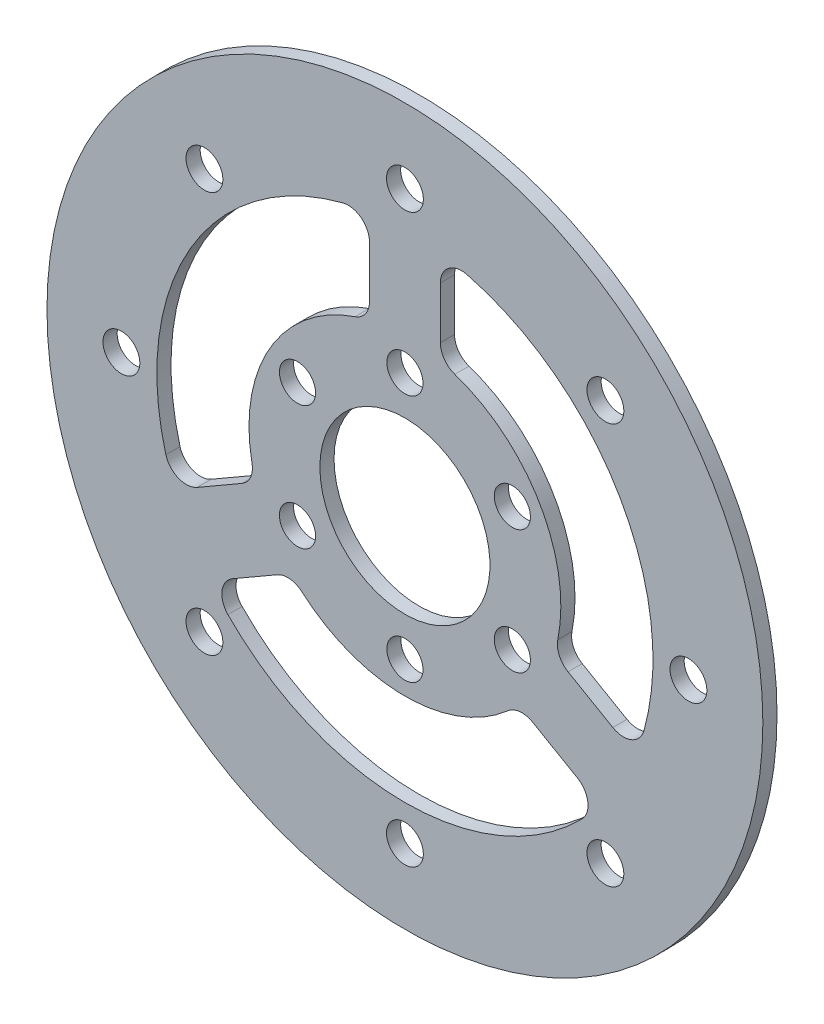
SolidWorks part; units mm, degrees
material "Thornel Mat VMA"
ref_plane "前视基准面" through (0, 0, 0) normal (0, 0, 1) x (1, 0, 0)
ref_plane "上视基准面" through (0, 0, 0) normal (0, 1, 0) x (1, 0, 0)
ref_plane "右视基准面" through (0, 0, 0) normal (1, 0, 0) x (0, 0, -1)
other "Configuration Table"
sketch "草图1" plane through (0, 0, 0) normal (0, 0, 1) x (1, 0, 0)
  circle A0 centre (0, 0) radius 40 construction
  circle A1 centre (0, 0) radius 50.5
  circle A2 centre (0, 40) radius 2.6
  circle A3 centre (0, 0) radius 35
  circle A4 centre (28.2843, 28.2843) radius 2.6
  circle A5 centre (40, 0) radius 2.6
  circle A6 centre (28.2843, -28.2843) radius 2.6
  circle A7 centre (0, -40) radius 2.6
  circle A8 centre (-28.2843, -28.2843) radius 2.6
  circle A9 centre (-40, 0) radius 2.6
  circle A10 centre (-28.2843, 28.2843) radius 2.6
  point P24 (0, 0)
  dimension "D1" = 80
  dimension "D2" = 101
  dimension "D3" = 70
  dimension "D4" = 5.2
  dimension "D5" = 8
extrude "凸台-拉伸1" add sketch "草图1" along normal blind 2
sketch "草图3" plane through (0, 0, 0) normal (0, 0, -1) x (-1, 0, 0)
  line L0 (0, 22) -> (0, 35) construction
  line L1 (5, 21.4243) -> (5, 34.641)
  line L2 (-5, 21.4243) -> (-5, 34.641)
  line L3 (5, 22) -> (5, 35) construction
  line L4 (-5, 22) -> (-5, 35) construction
  line L5 (21.054, -6.382) -> (32.5, -12.9904)
  line L6 (16.054, -15.0423) -> (27.5, -21.6506)
  line L7 (-16.054, -15.0423) -> (-27.5, -21.6506)
  line L8 (-21.054, -6.382) -> (-32.5, -12.9904)
  circle A0 centre (0, 0) radius 12
  circle A1 centre (0, 0) radius 17.5 construction
  circle A2 centre (0, 0) radius 22
  circle A3 centre (0, 0) radius 35 construction
  circle A4 centre (0, 17.5) radius 2.55
  circle A5 centre (15.1554, 8.75) radius 2.55
  circle A6 centre (15.1554, -8.75) radius 2.55
  circle A7 centre (0, 0) radius 35
  circle A8 centre (0, -17.5) radius 2.55
  circle A9 centre (-15.1554, -8.75) radius 2.55
  circle A10 centre (-15.1554, 8.75) radius 2.55
  point P18 (0, 0)
  point P24 (22.3317, -12.4527)
  point P26 (0, 0)
  point P36 (0, 0)
  circle M5 centre (0, 0) radius 35
  dimension "D1" = 24
  dimension "D2" = 35
  dimension "D3" = 44
  dimension "D4" = 5.1
  dimension "D6" = 5
  dimension "D7" = 5
  dimension "D5" = 6
  dimension "D8" = 3
extrude "凸台-拉伸4" add sketch "草图3" against normal up to surface (2 mm away) contours A2 L1 L2 M5 | A2 A6 A5 A4 A0 | A2 L6 L5 M5 | A2 L8 L7 M5
fillet "圆角2" radius 3 12 edges at (21.054, -6.382, 1) (32.5, -12.9904, 1) (5, 34.641, 1) (27.5, -21.6506, 1) (16.054, -15.0423, 1) (-16.054, -15.0423, 1) (-27.5, -21.6506, 1) (-32.5, -12.9904, 1) (-21.054, -6.382, 1) (-5, 21.4243, 1) (-5, 34.641, 1) (5, 21.4243, 1)
